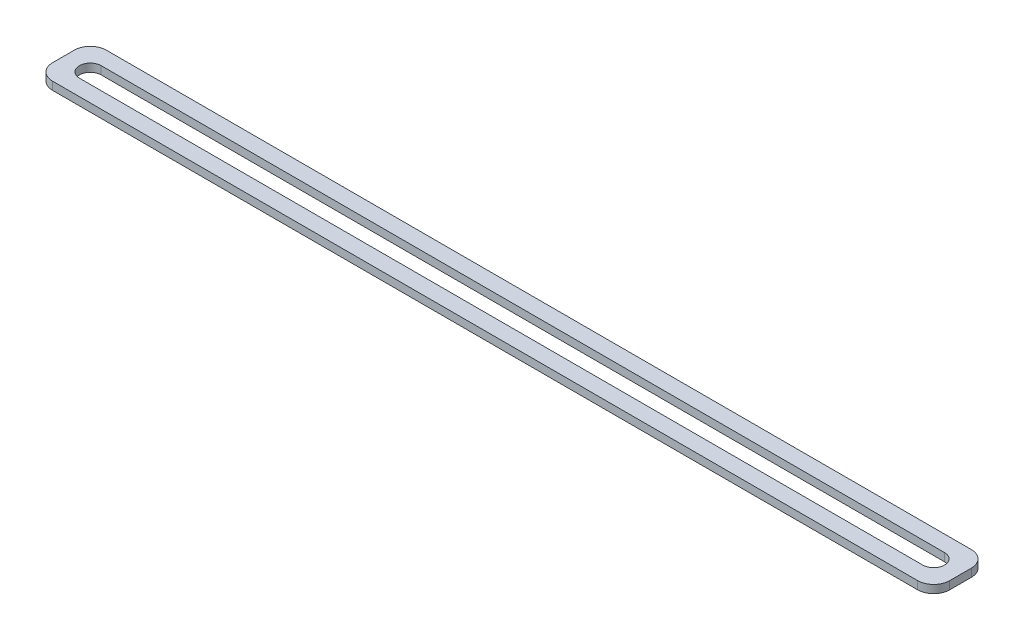
SolidWorks part; units mm, degrees
material "AISI 4130 Steel, annealed at 865C"
ref_plane "Front Plane" through (0, 0, 0) normal (0, 0, 1) x (1, 0, 0)
ref_plane "Top Plane" through (0, 0, 0) normal (0, 1, 0) x (1, 0, 0)
ref_plane "Right Plane" through (0, 0, 0) normal (1, 0, 0) x (0, 0, -1)
sketch "Sketch1" plane through (0, 0, 0) normal (0, 1, 0) x (1, 0, 0)
  line L0 (-83.575, 0) -> (83.575, 0) construction
  line L1 (-88.9, -5.325) -> (88.9, -5.325)
  line L2 (-88.9, -5.325) -> (-88.9, 5.325)
  line L3 (-88.9, 5.325) -> (88.9, 5.325)
  line L4 (88.9, -5.325) -> (88.9, 5.325)
  line L5 (-88.9, -5.325) -> (88.9, 5.325) construction
  line L6 (-88.9, 5.325) -> (88.9, -5.325) construction
  line L7 (-83.575, 2.15) -> (83.575, 2.15)
  line L8 (-83.575, -2.15) -> (83.575, -2.15)
  arc A0 (-83.575, 2.15) -> (-83.575, -2.15) centre (-83.575, 0) ccw
  arc A1 (83.575, -2.15) -> (83.575, 2.15) centre (83.575, 0) ccw
  point P0 (0, 0)
  point P8 (0, 0)
  dimension "D2" = 3.175
  dimension "D3" = 2.15
  dimension "D1" = 177.8
  dimension "D4" = 3.175
extrude "Boss-Extrude1" add sketch "Sketch1" along normal blind 1.5875
fillet "Fillet1" radius 3.175 4 edges at (88.9, 0.7937, -5.325) (88.9, 0.7937, 5.325) (-88.9, 0.7937, -5.325) (-88.9, 0.7937, 5.325)
